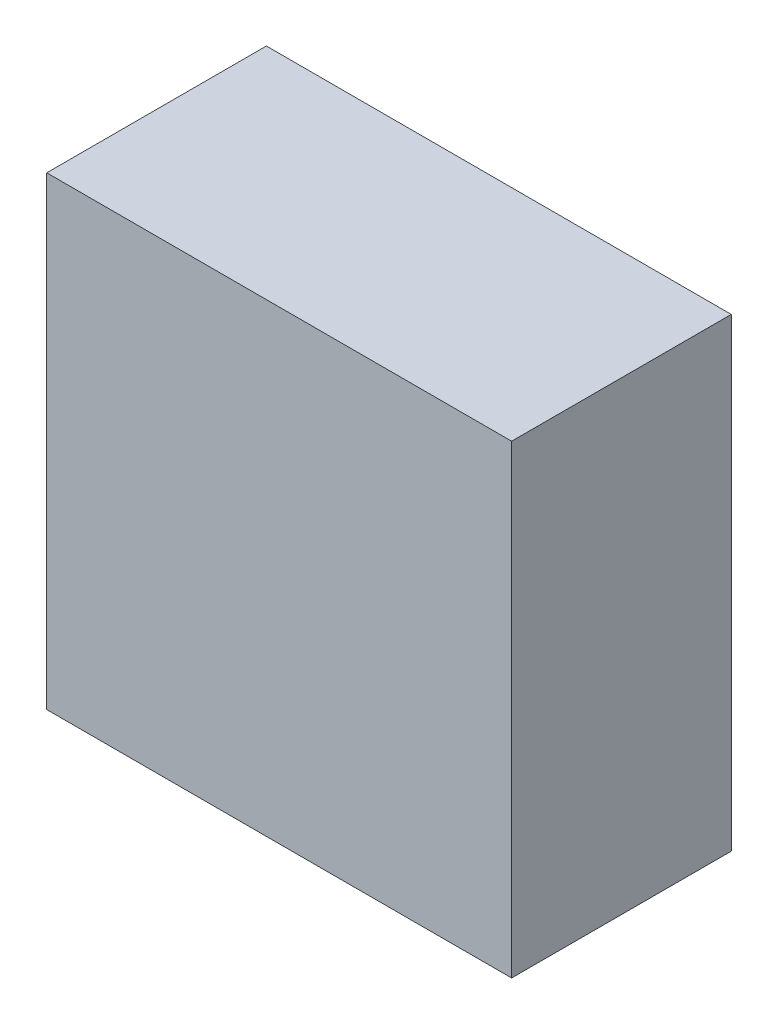
SolidWorks part; units mm, degrees
ref_plane "Front Plane" through (0, 0, 0) normal (0, 0, 1) x (1, 0, 0)
ref_plane "Top Plane" through (0, 0, 0) normal (0, 1, 0) x (1, 0, 0)
ref_plane "Right Plane" through (0, 0, 0) normal (1, 0, 0) x (0, 0, -1)
sketch "Sketch1" plane through (0, 0, 0) normal (0, 0, 1) x (1, 0, 0)
  line L1 (-6.35, 6.35) -> (6.35, 6.35)
  line L2 (-6.35, 6.35) -> (-6.35, -6.35)
  line L3 (-6.35, -6.35) -> (6.35, -6.35)
  line L4 (6.35, 6.35) -> (6.35, -6.35)
  dimension "D1" = 6.35
  dimension "D2" = 6.35
  dimension "D3" = 12.7
  dimension "D4" = 6.35
extrude "Boss-Extrude1" add sketch "Sketch1" along normal blind 6
hole_wizard "Tap Drill for M3x0.5 Tap3" positions "Sketch7" profile "Sketch6" hole size "M3x0.5" standard "BSI"
sketch "Sketch7" plane through (0, 0, 0) normal (0, 0, 1) x (1, 0, 0)
  point P0 (0, 0)
sketch "Sketch6" plane through (0, 0, 0) normal (1, 0, 0) x (0, 1, 0)
  line L0 (0, 0) -> (0, 4.7511)
  line L1 (0, 4.7511) -> (1.25, 4)
  line L2 (1.25, 4) -> (1.25, 0)
  line L5 (1.25, 0) -> (0, 0)
  line L10 (0, 4.7511) -> (-1.25, 4) construction
  line L11 (0, -6.35) -> (0, 107.95) construction
  dimension "Hole Dia." = 2.5
  dimension "Hole Depth" = 4
  dimension "Drill Angle" = 118
